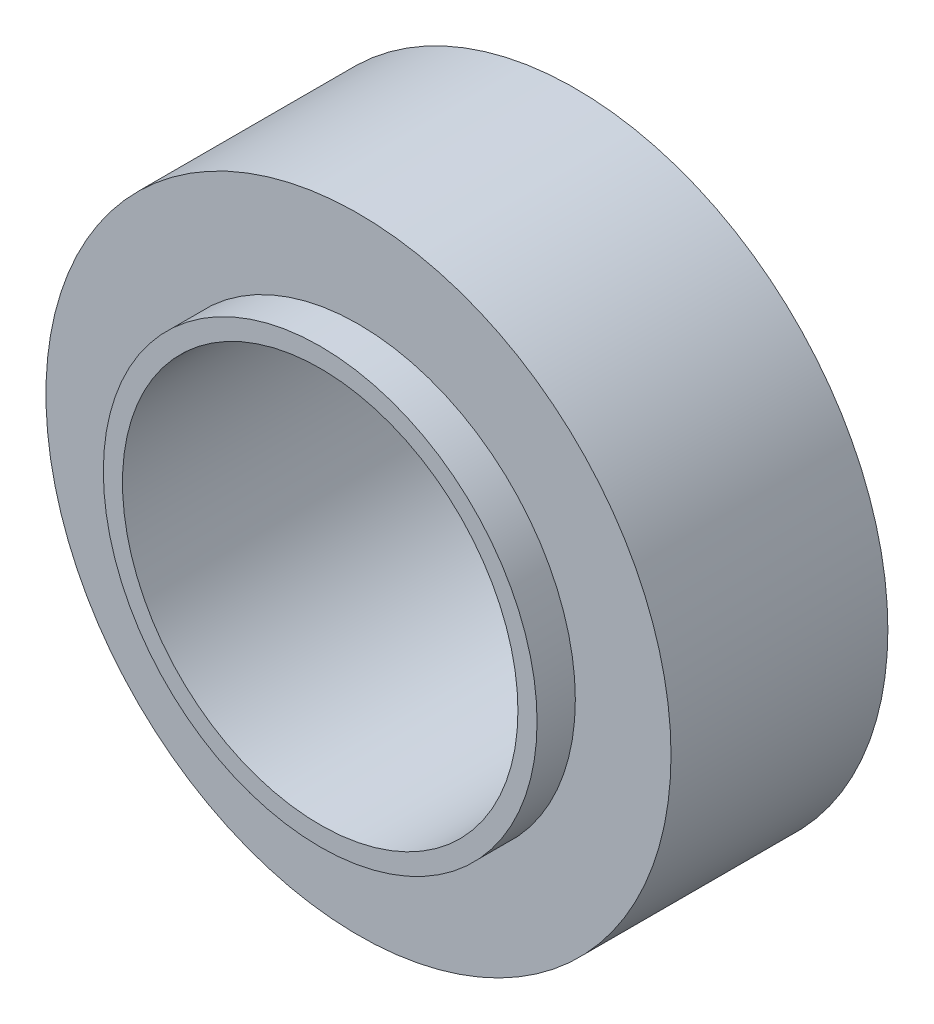
SolidWorks part; units mm, degrees
ref_plane "Piano frontale" through (0, 0, 0) normal (0, 0, 1) x (1, 0, 0)
ref_plane "Piano superiore" through (0, 0, 0) normal (0, 1, 0) x (1, 0, 0)
ref_plane "Piano destro" through (0, 0, 0) normal (1, 0, 0) x (0, 0, -1)
sketch "Schizzo1" plane through (0, 0, 0) normal (0, 0, 1) x (1, 0, 0)
  circle A0 centre (0, 0) radius 49
  circle A1 centre (0, 0) radius 31
  dimension "D1" = 98
  dimension "D2" = 62
extrude "Estrusione1" add sketch "Schizzo1" along normal mid plane 46 from offset 0
sketch "Schizzo4" plane through (0, 0, 0) normal (0, 1, 0) x (1, 0, 0)
  line L0 (0, 0) -> (38.9115, 0) construction
  line L1 (49, 23) -> (34, 23)
  line L2 (49, 23) -> (49, 17)
  line L3 (49, 17) -> (34, 17)
  line L4 (34, 23) -> (34, 17)
  line L5 (49, -17) -> (34, -17)
  line L6 (49, -23) -> (49, -17)
  line L7 (49, -23) -> (34, -23)
  line L8 (34, -23) -> (34, -17)
  dimension "D1" = 15
  dimension "D2" = 6
revolve "Taglia-Rivoluzione1" cut sketch "Schizzo4" angle 360 about axis through (0, 0, 23) along (0, 0, -1)
